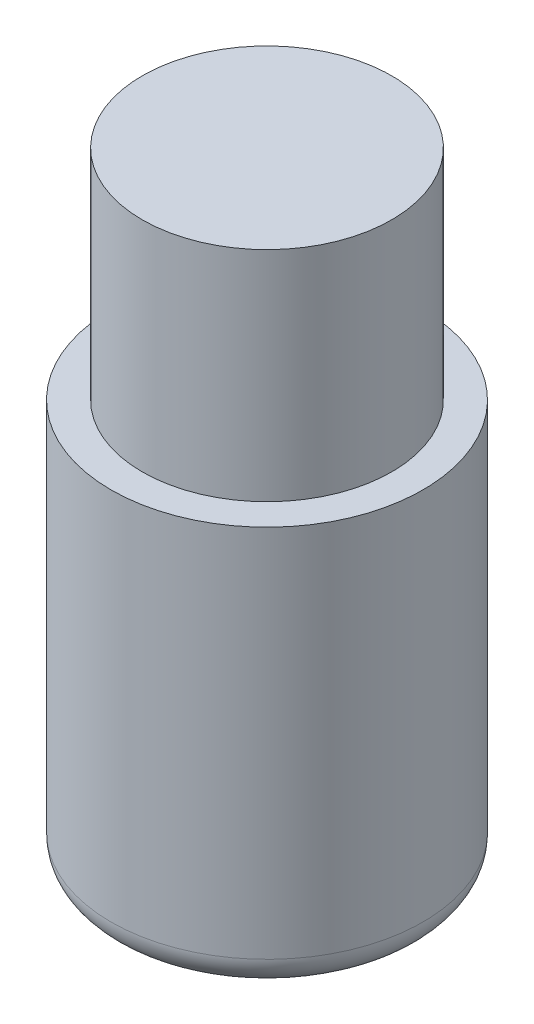
SolidWorks part; units mm, degrees
ref_plane "Front Plane" through (0, 0, 0) normal (0, 0, 1) x (1, 0, 0)
ref_plane "Top Plane" through (0, 0, 0) normal (0, 1, 0) x (1, 0, 0)
ref_plane "Right Plane" through (0, 0, 0) normal (1, 0, 0) x (0, 0, -1)
sketch "Sketch1" plane through (0, 0, 0) normal (0, 1, 0) x (1, 0, 0)
  circle A0 centre (0, 0) radius 5
  dimension "D1" = 10
extrude "Boss-Extrude1" add sketch "Sketch1" along normal blind 13
fillet "Fillet2" radius 1
sketch "Sketch2" plane through (0, 13, 0) normal (0, 1, 0) x (1, 0, 0)
  circle A0 centre (0, 0) radius 4
  dimension "D1" = 8
extrude "Boss-Extrude2" add sketch "Sketch2" along normal blind 7
